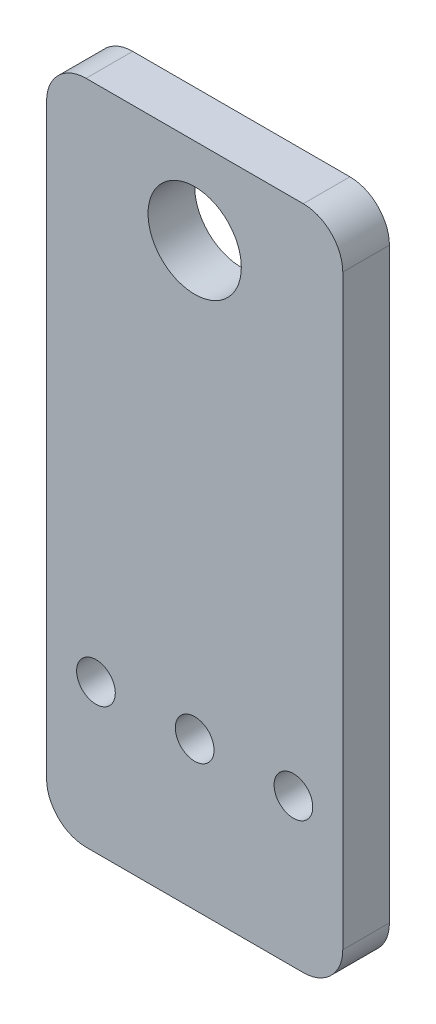
SolidWorks part; units mm, degrees
material "PC High Viscosity"
ref_plane "Front Plane" through (0, 0, 0) normal (0, 0, 1) x (1, 0, 0)
ref_plane "Top Plane" through (0, 0, 0) normal (0, 1, 0) x (1, 0, 0)
ref_plane "Right Plane" through (0, 0, 0) normal (1, 0, 0) x (0, 0, -1)
sketch "Sketch1" plane through (0, 0, 0) normal (0, 0, 1) x (1, 0, 0)
  line L0 (-382.27, -19.05) -> (-354.33, -19.05)
  line L1 (-349.25, -13.97) -> (-349.25, 61.53)
  line L2 (-354.33, 66.61) -> (-382.27, 66.61)
  line L3 (-387.35, 61.53) -> (-387.35, -13.97)
  circle A3 centre (-368.3, 0) radius 2.4892
  circle A4 centre (-355.6, 0) radius 2.4892
  circle A7 centre (-381, 0) radius 2.4892
  arc A9 (-354.33, -19.05) -> (-349.25, -13.97) centre (-354.33, -13.97) ccw
  arc A10 (-387.35, -13.97) -> (-382.27, -19.05) centre (-382.27, -13.97) ccw
  arc A11 (-382.27, 66.61) -> (-387.35, 61.53) centre (-382.27, 61.53) ccw
  arc A12 (-349.25, 61.53) -> (-354.33, 66.61) centre (-354.33, 61.53) ccw
  circle A13 centre (-368.3, 55.53) radius 6
  dimension "D6" = 5.08
  dimension "D7" = 11.08
  dimension "D8" = 12
  dimension "D9" = 74.58
extrude "Boss-Extrude1" add sketch "Sketch1" along normal blind 6
